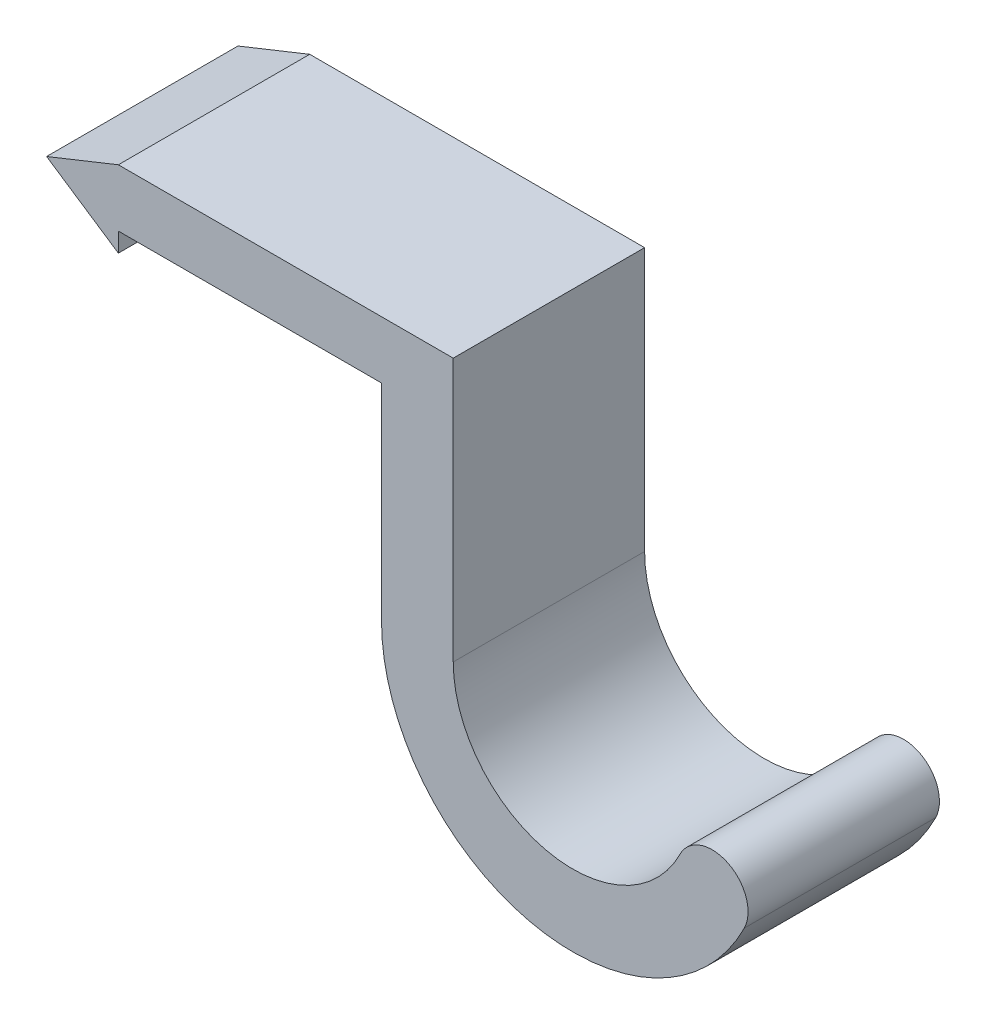
SolidWorks part; units mm, degrees
ref_plane "Front Plane" through (0, 0, 0) normal (0, 0, 1) x (1, 0, 0)
ref_plane "Top Plane" through (0, 0, 0) normal (0, 1, 0) x (1, 0, 0)
ref_plane "Right Plane" through (0, 0, 0) normal (1, 0, 0) x (0, 0, -1)
sketch "Sketch1" plane through (0, 0, 0) normal (0, 0, 1) x (1, 0, 0)
  line L0 (0, 0) -> (55, 0)
  line L1 (55, 0) -> (55, -43)
  line L2 (0, 0) -> (0, -4)
  line L3 (0, -4) -> (-15, 6)
  line L4 (-15, 6) -> (0, 12)
  line L5 (0, 12) -> (70, 12)
  line L6 (70, 12) -> (70, -43)
  line L7 (0, 12) -> (0, 0) construction
  line L8 (0, 6) -> (-15, 6) construction
  arc A0 (55, -43) -> (130.8438, -60.7545) centre (95, -43) ccw
  arc A1 (70, -43) -> (117.4024, -54.0966) centre (95, -43) ccw
  arc A2 (117.4024, -54.0966) -> (130.8438, -60.7545) centre (124.1231, -57.4256) cw
  point P15 (148.7223, -52.9976)
  point P16 (124.1231, -57.4256)
  dimension "D7" = 25
  dimension "D1" = 55
  dimension "D2" = 12
  dimension "D3" = 4
  dimension "D4" = 15
  dimension "D5" = 15
  dimension "D6" = 55
extrude "Boss-Extrude1" add sketch "Sketch1" along normal blind 40
